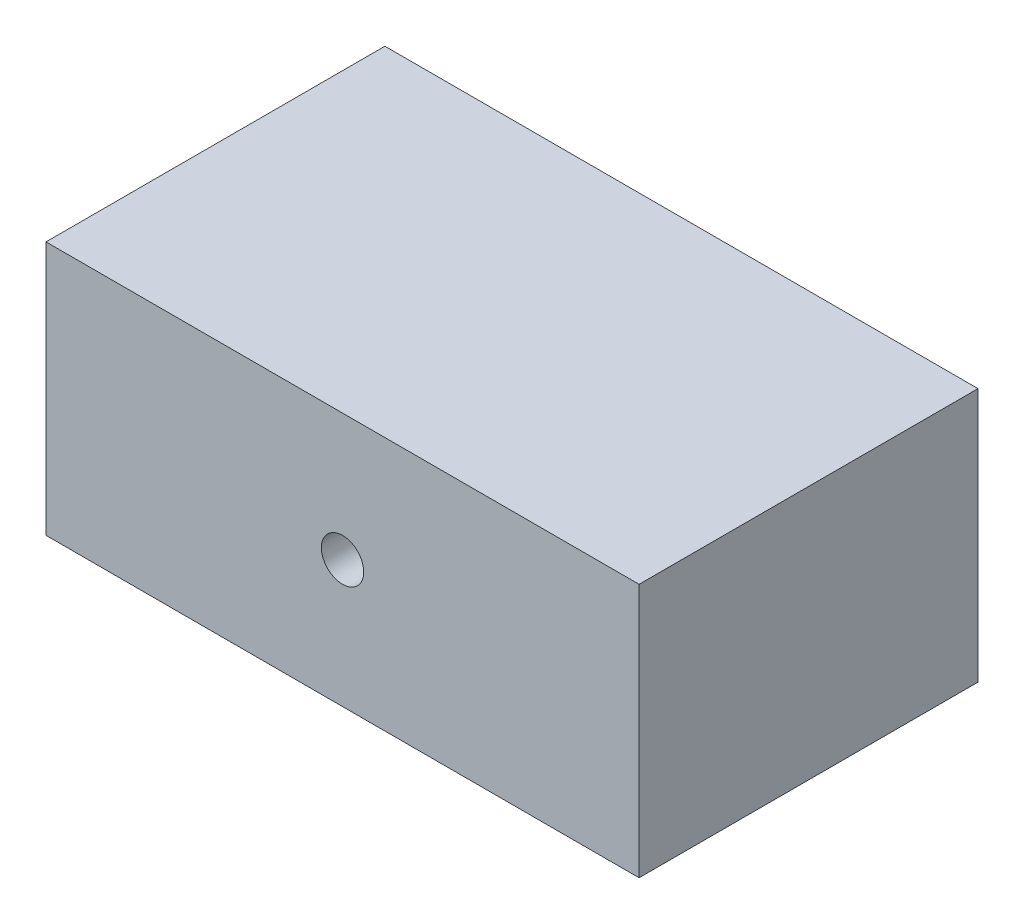
SolidWorks part; units mm, degrees
material "Balsa"
ref_plane "Front Plane" through (0, 0, 0) normal (0, 0, 1) x (1, 0, 0)
ref_plane "Top Plane" through (0, 0, 0) normal (0, 1, 0) x (1, 0, 0)
ref_plane "Right Plane" through (0, 0, 0) normal (1, 0, 0) x (0, 0, -1)
sketch "Sketch1" plane through (0, 0, 0) normal (0, 0, 1) x (1, 0, 0)
  line L1 (0, 0) -> (88.9, 0)
  line L2 (0, 0) -> (0, 38.1)
  line L3 (0, 38.1) -> (88.9, 38.1)
  line L4 (88.9, 0) -> (88.9, 38.1)
  circle A0 centre (44.45, 19.05) radius 3.175
  dimension "D3" = 6.35
  dimension "D4" = 19.05
  dimension "D5" = 44.45
  dimension "D1" = 88.9
  dimension "D2" = 38.1
extrude "Boss-Extrude1" add sketch "Sketch1" along normal blind 50.8
